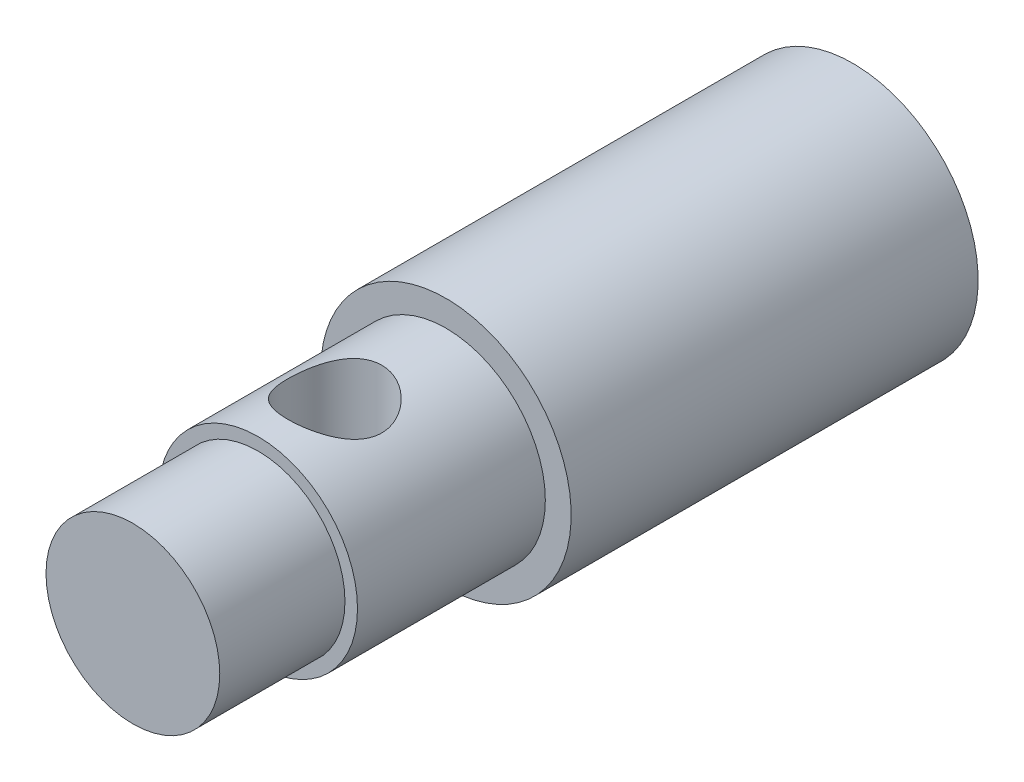
SolidWorks part; units mm, degrees
ref_plane "Front Plane" through (0, 0, 0) normal (0, 0, 1) x (1, 0, 0)
ref_plane "Top Plane" through (0, 0, 0) normal (0, 1, 0) x (1, 0, 0)
ref_plane "Right Plane" through (0, 0, 0) normal (1, 0, 0) x (0, 0, -1)
sketch "Sketch1" plane through (0, 0, 0) normal (0, 0, 1) x (1, 0, 0)
  circle A0 centre (0, 0) radius 4
  dimension "D1" = 8
extrude "Boss-Extrude2" add sketch "Sketch1" along normal blind 13
sketch "Sketch2" plane through (0, 0, 13) normal (0, 0, 1) x (1, 0, 0)
  circle A0 centre (0, 0) radius 3.175
  dimension "D1" = 6.35
extrude "Boss-Extrude3" add sketch "Sketch2" along normal blind 6
sketch "Sketch3" plane through (0, 0, 19) normal (0, 0, 1) x (1, 0, 0)
  circle A0 centre (0, 0) radius 2.775
  circle A1 centre (0, 0) radius 3.175 construction
  dimension "D1" = 0.4
extrude "Boss-Extrude4" add sketch "Sketch3" along normal blind 4
sketch "Sketch4" plane through (0, 0, 0) normal (0, 1, 0) x (1, 0, 0)
  line L0 (-2.775, -19) -> (2.775, -19) construction
  circle A0 centre (0, -16.55) radius 1.5
  dimension "D2" = 3
  dimension "D1" = 2.45
extrude "Cut-Extrude1" cut sketch "Sketch4" against normal through all both and the other way through all
